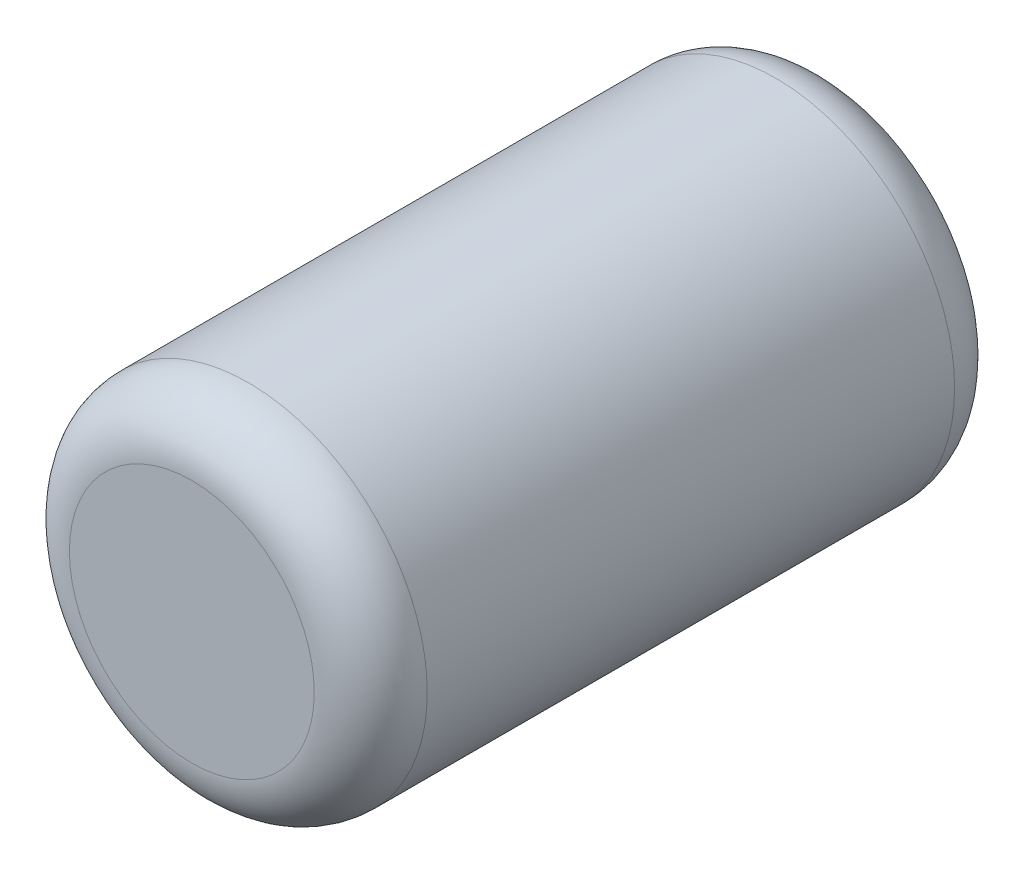
SolidWorks part; units mm, degrees
ref_plane "Front Plane" through (0, 0, 0) normal (0, 0, 1) x (1, 0, 0)
ref_plane "Top Plane" through (0, 0, 0) normal (0, 1, 0) x (1, 0, 0)
ref_plane "Right Plane" through (0, 0, 0) normal (1, 0, 0) x (0, 0, -1)
sketch "Sketch2" plane through (0, 0, 0) normal (0, 0, 1) x (1, 0, 0)
  circle A0 centre (0, 0) radius 9.5
  dimension "D1" = 19
extrude "Boss-Extrude1" add sketch "Sketch2" along normal blind 34
ref_point "Point1"
ref_point "Point2"
fillet "Fillet1" radius 3 2 edges at (9.5, 0, 34) (9.5, 0, 0)
